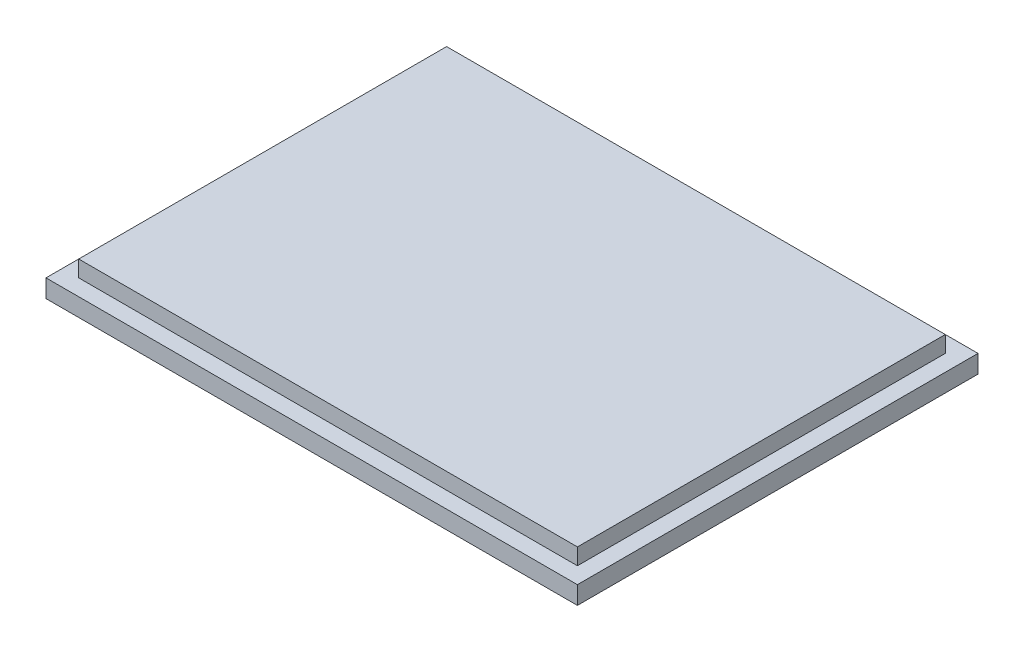
SolidWorks part; units mm, degrees
ref_plane "Front Plane" through (0, 0, 0) normal (0, 0, 1) x (1, 0, 0)
ref_plane "Top Plane" through (0, 0, 0) normal (0, 1, 0) x (1, 0, 0)
ref_plane "Right Plane" through (0, 0, 0) normal (1, 0, 0) x (0, 0, -1)
sketch "Sketch1" plane through (0, 0, 0) normal (0, 1, 0) x (1, 0, 0)
  line L0 (0, 0) -> (0, 122.5) construction
  line L1 (-162.5, 122.5) -> (162.5, 122.5)
  line L2 (-162.5, 122.5) -> (-162.5, -122.5)
  line L3 (-162.5, -122.5) -> (162.5, -122.5)
  line L4 (162.5, 122.5) -> (162.5, -122.5)
  line L5 (0, 0) -> (162.5, 0) construction
  dimension "D1" = 325
  dimension "D2" = 245
extrude "Boss-Extrude1" add sketch "Sketch1" along normal blind 11 contours L1 L4 L3 L2
sketch "Sketch2" plane through (0, 11, 0) normal (0, 1, 0) x (1, 0, 0)
  line L0 (-162.5, 122.5) -> (162.5, 122.5) construction
  line L1 (-162.5, 122.5) -> (-162.5, -122.5) construction
  line L2 (-162.5, -122.5) -> (162.5, -122.5) construction
  line L3 (162.5, 122.5) -> (162.5, -122.5) construction
  line L4 (-162.5, 122.5) -> (162.5, 122.5)
  line L5 (-162.5, 122.5) -> (-162.5, -122.5)
  line L6 (-162.5, -122.5) -> (162.5, -122.5)
  line L7 (162.5, 122.5) -> (162.5, -122.5)
  line L8 (-152.5, 112.5) -> (152.5, 112.5)
  line L9 (152.5, 112.5) -> (152.5, -112.5)
  line L10 (-152.5, -112.5) -> (152.5, -112.5)
  line L11 (-152.5, 112.5) -> (-152.5, -112.5)
  dimension "D1" = 10
extrude "Boss-Extrude2" add sketch "Sketch2" along normal blind 10 contours L8 L11 L10 L9
